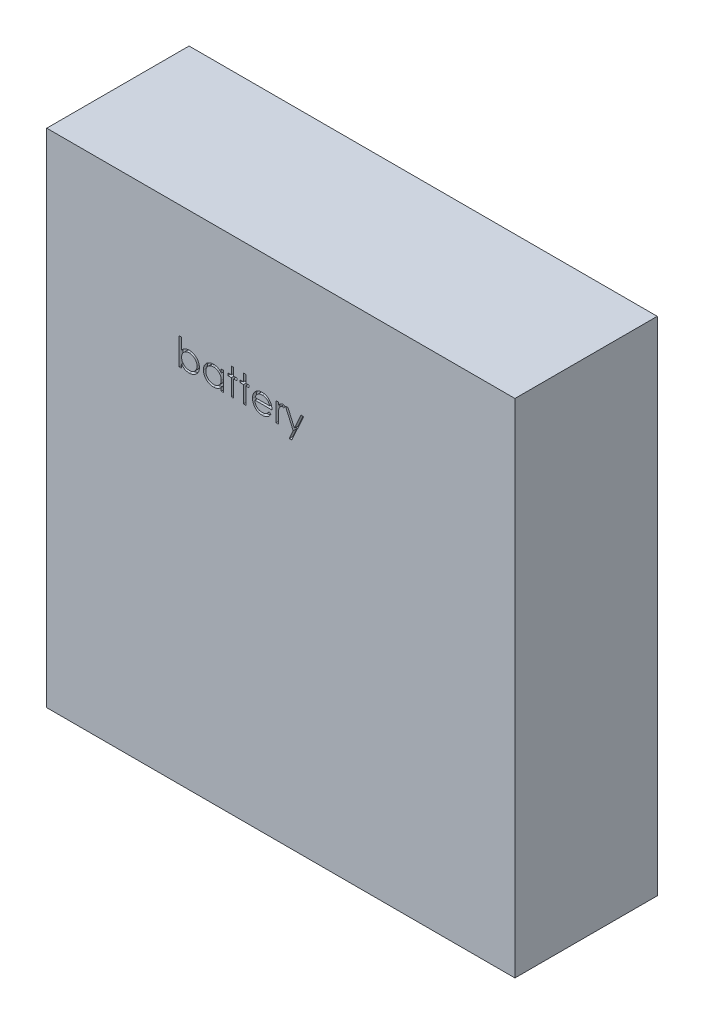
SolidWorks part; units mm, degrees
ref_plane "Front Plane" through (0, 0, 0) normal (0, 0, 1) x (1, 0, 0)
ref_plane "Top Plane" through (0, 0, 0) normal (0, 1, 0) x (1, 0, 0)
ref_plane "Right Plane" through (0, 0, 0) normal (1, 0, 0) x (0, 0, -1)
sketch "Sketch1" plane through (0, 0, 0) normal (0, 0, 1) x (1, 0, 0)
  line L1 (0, 0) -> (62.5, 0)
  line L2 (0, 0) -> (0, 67)
  line L3 (0, 67) -> (62.5, 67)
  line L4 (62.5, 0) -> (62.5, 67)
  dimension "D1" = 62.5
  dimension "D2" = 67
extrude "Boss-Extrude1" add sketch "Sketch1" along normal blind 19
sketch "Sketch2" plane through (0, 0, 19) normal (0, 0, 1) x (1, 0, 0)
  text T0 "battery\r\n"
extrude "Cut-Extrude1" cut sketch "Sketch2" against normal blind 0.5
